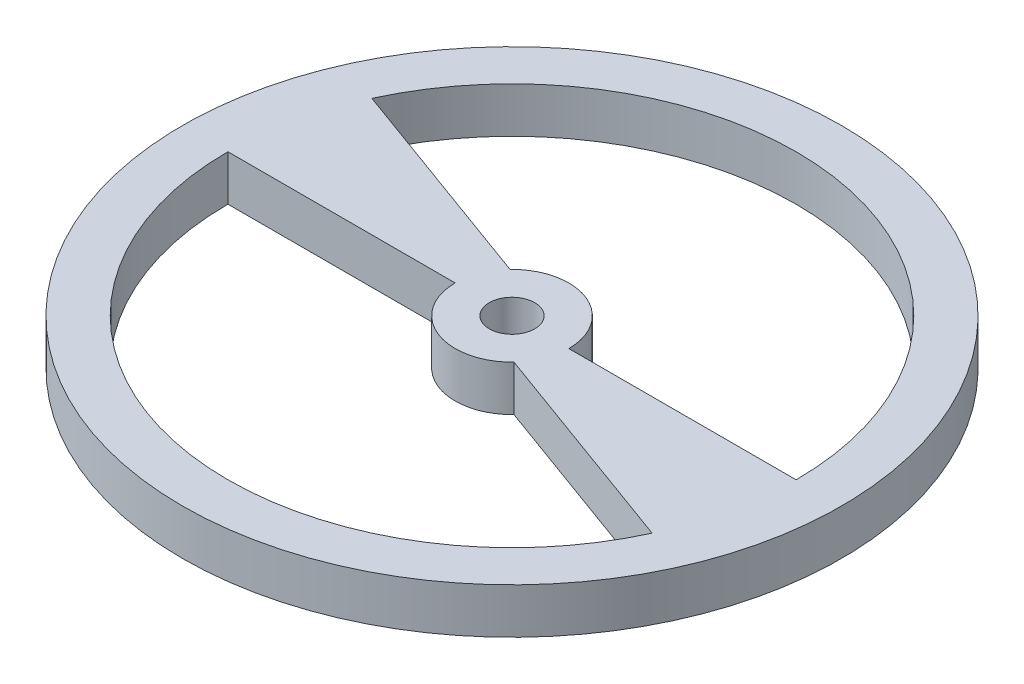
SolidWorks part; units mm, degrees
ref_plane "Front Plane" through (0, 0, 0) normal (0, 0, 1) x (1, 0, 0)
ref_plane "Top Plane" through (0, 0, 0) normal (0, 1, 0) x (1, 0, 0)
ref_plane "Right Plane" through (0, 0, 0) normal (1, 0, 0) x (0, 0, -1)
sketch "Sketch1" plane through (0, 0, 0) normal (0, 1, 0) x (1, 0, 0)
  line L0 (-2.5, 0) -> (-12.5, 0)
  line L1 (-11.3665, 5.2012) -> (-1.8111, 1.7234)
  line L2 (2.5, 0) -> (12.5, 0)
  line L3 (1.8111, -1.7234) -> (11.3665, -5.2012)
  circle A0 centre (0, 0) radius 14.5
  arc A1 (-12.5, 0) -> (11.3665, -5.2012) centre (0, 0) ccw
  circle A2 centre (0, 0) radius 1
  arc A3 (2.5, 0) -> (-1.8111, 1.7234) centre (0, 0) ccw
  arc A4 (12.5, 0) -> (-11.3665, 5.2012) centre (0, 0) ccw
  arc A5 (-2.5, 0) -> (1.8111, -1.7234) centre (0, 0) ccw
  dimension "D2" = 25
  dimension "D3" = 2
  dimension "D4" = 5
  dimension "D5" = 20
  dimension "D6" = 20
  dimension "D1" = 2
extrude "Boss-Extrude1" add sketch "Sketch1" along normal blind 2
equation "\"D6@Sketch1\"=\"D5@Sketch1\""
